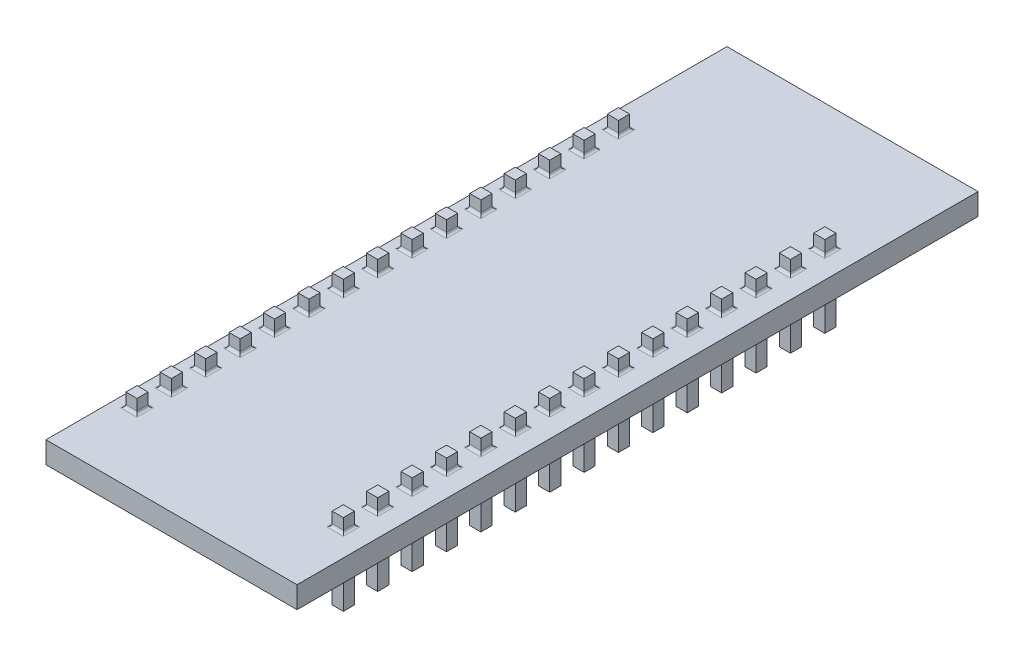
SolidWorks part; units mm, degrees
ref_plane "Front Plane" through (0, 0, 0) normal (0, 0, 1) x (1, 0, 0)
ref_plane "Top Plane" through (0, 0, 0) normal (0, 1, 0) x (1, 0, 0)
ref_plane "Right Plane" through (0, 0, 0) normal (1, 0, 0) x (0, 0, -1)
sketch "Sketch1" plane through (0, 0, 0) normal (0, 1, 0) x (1, 0, 0)
  line L1 (-6.4206, 7.7313) -> (12.1194, 7.7313)
  line L2 (-6.4206, 7.7313) -> (-6.4206, -42.5587)
  line L3 (-6.4206, -42.5587) -> (12.1194, -42.5587)
  line L4 (12.1194, 7.7313) -> (12.1194, -42.5587)
  dimension "D1" = 18.54
  dimension "D2" = 50.29
extrude "Boss-Extrude1" add sketch "Sketch1" along normal blind 1.6
sketch "Sketch2" plane through (0, 1.6, 0) normal (0, 1, 0) x (1, 0, 0)
  line L0 (-6.4206, -42.5587) -> (12.1194, -42.5587) construction
  line L1 (-5.5274, -36.7346) -> (-4.7033, -36.7346)
  line L2 (-5.5274, -36.7346) -> (-5.5274, -37.5587)
  line L3 (-5.5274, -37.5587) -> (-4.7033, -37.5587)
  line L4 (-4.7033, -36.7346) -> (-4.7033, -37.5587)
  dimension "D1" = 0.8241
  dimension "D2" = 5
extrude "Boss-Extrude2" add sketch "Sketch2" along normal blind 1 and the other way blind 5
fillet "Fillet1" radius 0.2 4 edges at (-5.1154, 1.6, 36.7346) (-4.7033, 1.6, 37.1466) (-5.1154, 1.6, 37.5587) (-5.5274, 1.6, 37.1466)
pattern_linear "LPattern1" count 15 spacing 2.54 along (0, 0, -1) count 2 spacing 15.24 along (1, 0, 0) of "Boss-Extrude2", "Fillet1"
